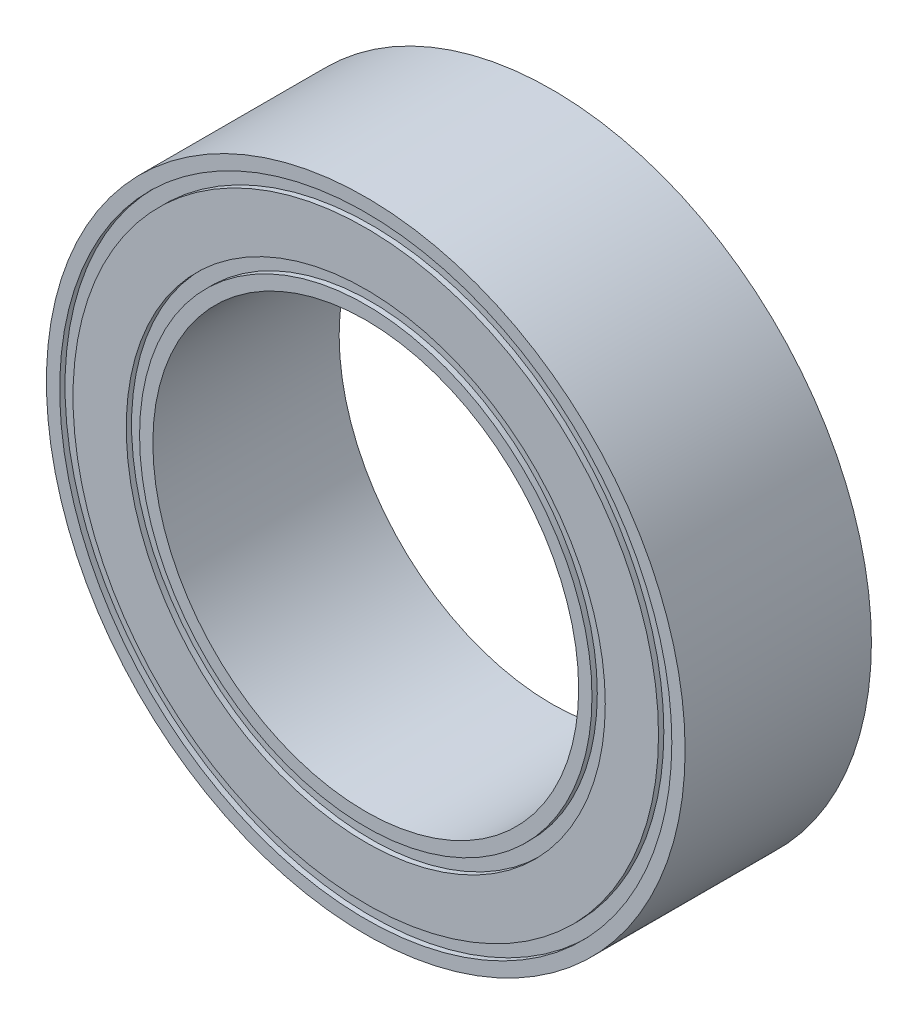
SolidWorks part; units mm, degrees
ref_plane "前视基准面" through (0, 0, 0) normal (0, 0, 1) x (1, 0, 0)
ref_plane "上视基准面" through (0, 0, 0) normal (0, 1, 0) x (1, 0, 0)
ref_plane "右视基准面" through (0, 0, 0) normal (1, 0, 0) x (0, 0, -1)
sketch "草图1" plane through (0, 0, 0) normal (0, 0, 1) x (1, 0, 0)
  circle A0 centre (0, 0) radius 6
  circle A1 centre (0, 0) radius 4
  dimension "D1" = 12
  dimension "D2" = 8
extrude "凸台-拉伸1" add sketch "草图1" along normal blind 3.5
sketch "草图2" plane through (0, 0, 3.5) normal (0, 0, 1) x (1, 0, 0)
  circle A0 centre (0, 0) radius 5.5
  circle A1 centre (0, 0) radius 4.25
  circle A2 centre (0, 0) radius 5.75
  circle A3 centre (0, 0) radius 4.5
  dimension "D1" = 11.5
  dimension "D2" = 8.5
  dimension "D3" = 9
  dimension "D4" = 11
extrude "切除-拉伸1" cut sketch "草图2" against normal blind 0.1 contours A2 A0 | A3 A1
sketch "草图3" plane through (0, 0, 0) normal (0, 0, -1) x (-1, 0, 0)
  circle A0 centre (0, 0) radius 4.25
  circle A1 centre (0, 0) radius 4.5
  circle A2 centre (0, 0) radius 5.5
  circle A3 centre (0, 0) radius 5.75
  dimension "D1" = 11.5
  dimension "D2" = 11
  dimension "D3" = 9
  dimension "D4" = 8.5
extrude "切除-拉伸2" cut sketch "草图3" against normal blind 0.1 contours A3 A2 | A1 A0
